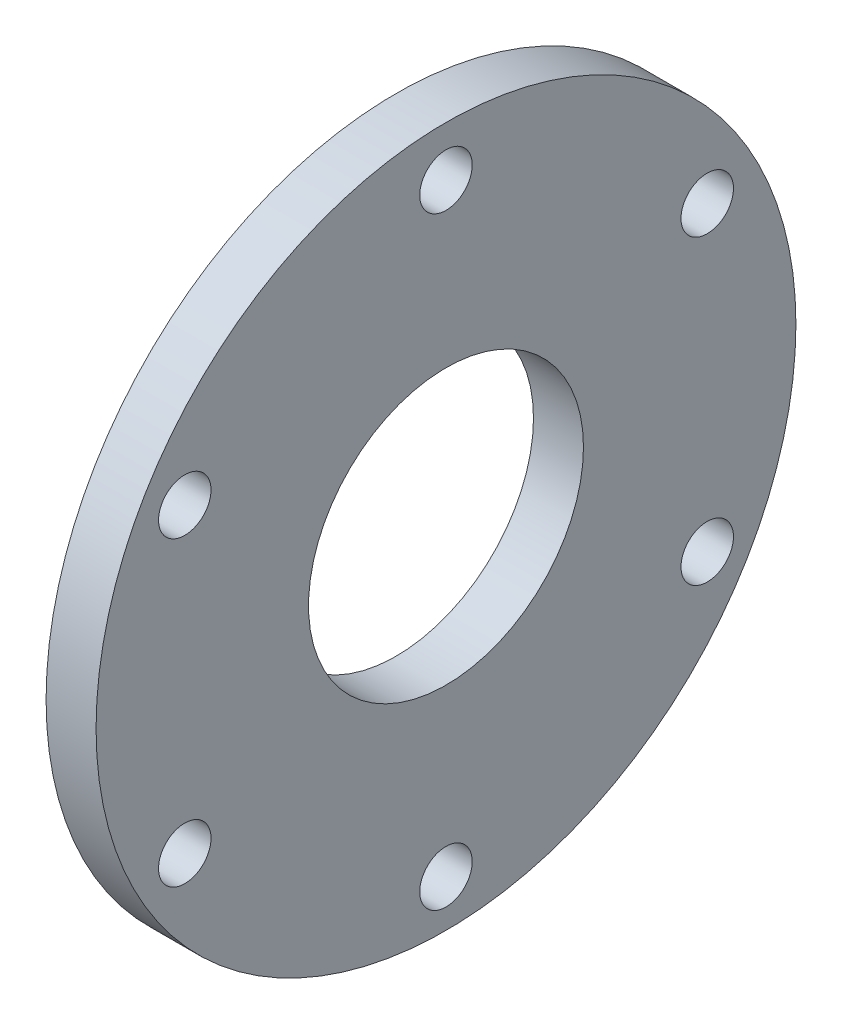
SolidWorks part; units mm, degrees
ref_plane "Alzado" through (0, 0, 0) normal (0, 0, 1) x (1, 0, 0)
ref_plane "Planta" through (0, 0, 0) normal (0, 1, 0) x (1, 0, 0)
ref_plane "Vista lateral" through (0, 0, 0) normal (1, 0, 0) x (0, 0, -1)
sketch "Croquis1" plane through (0, 0, 0) normal (1, 0, 0) x (0, 0, -1)
  circle A0 centre (0, 0) radius 70
  dimension "D1" = 140
extrude "Saliente-Extruir1" add sketch "Croquis1" along normal blind 10
sketch "Croquis2" plane through (10, 0, 0) normal (1, 0, 0) x (0, 0, -1)
  circle A0 centre (0, 0) radius 60
  dimension "D1" = 120
sketch "Croquis7" plane through (10, 0, 0) normal (1, 0, 0) x (0, 0, -1)
  line L0 (0, 0) -> (0, 82.9568)
hole_wizard "Taladro roscado M12x1.51" positions "Croquis3D2" profile "Croquis8" tap size "M12x1.5" standard "Ansi Metric"
sketch3d "Croquis3D2"
  line L0 (10, 0, 0) -> (10, 82.9568, 0) construction
  circle A0 centre (10, 0, 0) radius 60 construction
  point P0 (10, 60, 0)
  point P4 (70, 0, 0)
sketch "Croquis8" plane through (10, 60, 0) normal (0, 1, 0) x (0, 0, -1)
  line L0 (0, 0) -> (0, 34.6545)
  line L1 (0, 34.6545) -> (5.25, 31.5)
  line L2 (5.25, 31.5) -> (5.25, 0)
  line L5 (5.25, 0) -> (0, 0)
  line L10 (0, 34.6545) -> (-5.25, 31.5) construction
  line L11 (0, -6.35) -> (0, 107.95) construction
  dimension "Diámetro de perforador para roscar" = 10.5
  dimension "Profundidad de perforador para roscar" = 31.5
  dimension "Ángulo de perforador" = 118
pattern_circular "MatrizC5" count 6 over 360 about axis through (0, -0.3394, 0) along (1, 0, 0) of "Taladro roscado M12x1.51"
sketch "Croquis9" plane through (10, 0, 0) normal (1, 0, 0) x (0, 0, -1)
  circle A0 centre (0, 0) radius 27.5
  dimension "D1" = 55
extrude "Cortar-Extruir1" cut sketch "Croquis9" against normal blind 10
